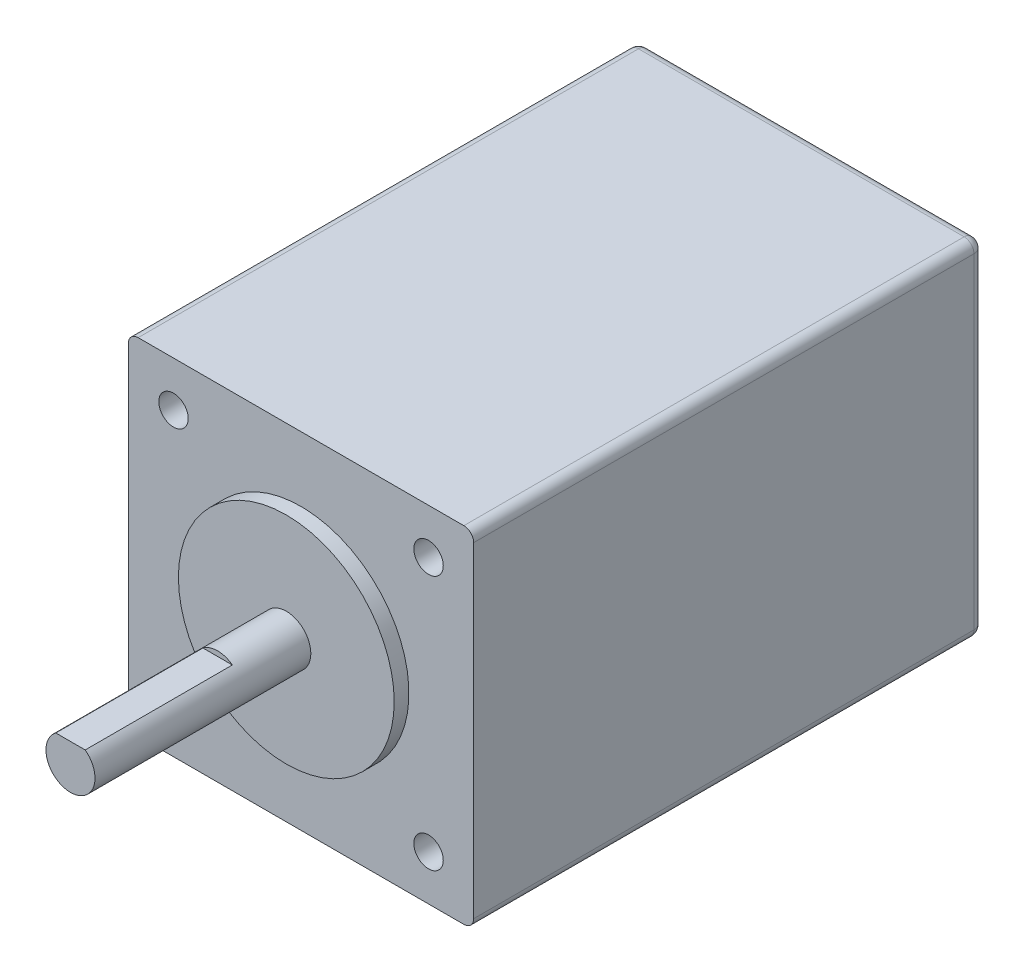
SolidWorks part; units mm, degrees
ref_plane "Front Plane" through (0, 0, 0) normal (0, 0, 1) x (1, 0, 0)
ref_plane "Top Plane" through (0, 0, 0) normal (0, 1, 0) x (1, 0, 0)
ref_plane "Right Plane" through (0, 0, 0) normal (1, 0, 0) x (0, 0, -1)
sketch "Sketch1" plane through (0, 0, 0) normal (0, 0, 1) x (1, 0, 0)
  line L1 (-17.6, -17.6) -> (17.6, -17.6)
  line L2 (-17.6, -17.6) -> (-17.6, 17.6)
  line L3 (-17.6, 17.6) -> (17.6, 17.6)
  line L4 (17.6, -17.6) -> (17.6, 17.6)
  line L5 (-17.6, -17.6) -> (17.6, 17.6) construction
  line L6 (-17.6, 17.6) -> (17.6, -17.6) construction
  point P0 (0, 0)
  dimension "D1" = 35.2
  dimension "D2" = 35.2
extrude "Boss-Extrude1" add sketch "Sketch1" along normal blind 52
sketch "Sketch2" plane through (0, 0, 52) normal (0, 0, 1) x (1, 0, 0)
  circle A0 centre (0, 0) radius 11
  dimension "D1" = 22
extrude "Boss-Extrude2" add sketch "Sketch2" along normal blind 1.5
sketch "Sketch3" plane through (0, 0, 53.5) normal (0, 0, 1) x (1, 0, 0)
  circle A0 centre (0, 0) radius 2.5
  dimension "D1" = 5
extrude "Boss-Extrude3" add sketch "Sketch3" along normal blind 22
sketch "Sketch4" plane through (0, 0, 0) normal (1, 0, 0) x (0, 0, -1)
  line L1 (-75.5, 2.5) -> (-60.5, 2.5)
  line L2 (-75.5, 2.5) -> (-75.5, 2)
  line L3 (-75.5, 2) -> (-60.5, 2)
  line L4 (-60.5, 2.5) -> (-60.5, 2)
  dimension "D1" = 15
  dimension "D2" = 0.5
extrude "Cut-Extrude1" cut sketch "Sketch4" against normal mid plane 10
sketch "Sketch5" plane through (0, 0, 52) normal (0, 0, 1) x (1, 0, 0)
  line L1 (-13, -13) -> (13, -13) construction
  line L2 (-13, -13) -> (-13, 13) construction
  line L3 (-13, 13) -> (13, 13) construction
  line L4 (13, -13) -> (13, 13) construction
  line L5 (-13, -13) -> (13, 13) construction
  line L6 (-13, 13) -> (13, -13) construction
  circle A0 centre (-13, 13) radius 1.5
  circle A1 centre (13, 13) radius 1.5
  circle A2 centre (13, -13) radius 1.5
  circle A3 centre (-13, -13) radius 1.5
  point P0 (0, 0)
  dimension "D3" = 3
  dimension "D1" = 26
  dimension "D2" = 26
  dimension "D4" = 4
extrude "Cut-Extrude2" cut sketch "Sketch5" against normal blind 4.5
fillet "Fillet1" radius 1 8 edges at (0, 17.6, 0) (-17.6, 0, 0) (0, -17.6, 0) (17.6, 0, 0) (-17.6, -17.6, 26) (17.6, -17.6, 26) (-17.6, 17.6, 26) (17.6, 17.6, 26)
